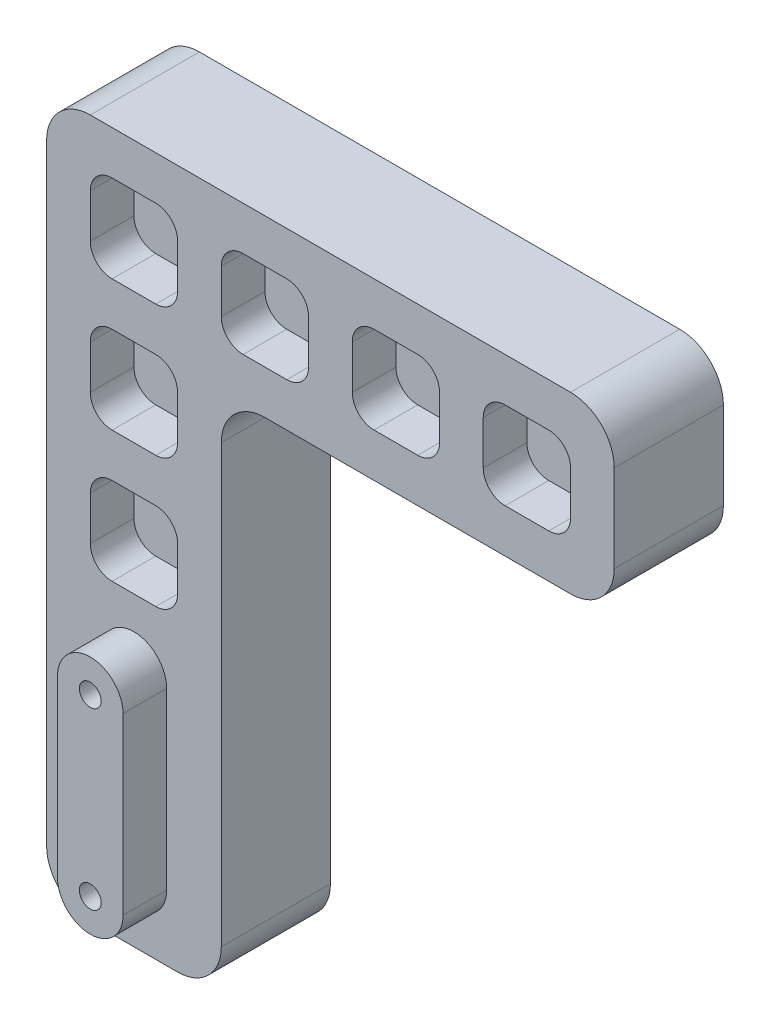
SolidWorks part; units mm, degrees
material "ABS"
ref_plane "Front Plane" through (0, 0, 0) normal (0, 0, 1) x (1, 0, 0)
ref_plane "Top Plane" through (0, 0, 0) normal (0, 1, 0) x (1, 0, 0)
ref_plane "Right Plane" through (0, 0, 0) normal (1, 0, 0) x (0, 0, -1)
sketch "Base Sketch" plane through (0, 0, 0) normal (0, 0, 1) x (1, 0, 0)
  line L0 (0, 0) -> (0, 160)
  line L1 (0, 160) -> (130, 160)
  line L2 (130, 160) -> (130, 120)
  line L3 (130, 120) -> (40, 120)
  line L4 (40, 120) -> (40, 0)
  line L5 (40, 0) -> (0, 0)
  dimension "D1" = 130
  dimension "D2" = 160
  dimension "D3" = 120
  dimension "D4" = 40
extrude "Base Extrude" add sketch "Base Sketch" along normal blind 25
sketch "Square Sketch" plane through (0, 0, 25) normal (0, 0, 1) x (1, 0, 0)
  line L0 (0, 160) -> (0, 0) construction
  line L1 (15, 150) -> (25, 150)
  line L2 (10, 145) -> (10, 135)
  line L3 (15, 130) -> (25, 130)
  line L4 (30, 145) -> (30, 135)
  line L5 (130, 160) -> (0, 160) construction
  arc A0 (25, 130) -> (30, 135) centre (25, 135) ccw
  arc A1 (15, 150) -> (10, 145) centre (15, 145) ccw
  arc A2 (15, 130) -> (10, 135) centre (15, 135) cw
  arc A3 (30, 145) -> (25, 150) centre (25, 145) ccw
  point P10 (30, 130)
  point P15 (10, 130)
  point P18 (30, 150)
  dimension "D5" = 5
  dimension "D1" = 10
  dimension "D2" = 10
  dimension "D3" = 20
  dimension "D4" = 20
extrude "Square Cut" cut sketch "Square Sketch" against normal blind 10
pattern_linear "Horizontal Pattern" count 4 spacing 30 along (1, 0, 0) of "Square Cut"
pattern_linear "Vertical Pattern" count 3 spacing 30 along (0, -1, 0) of "Square Cut"
sketch "Slot Sketch" plane through (0, 0, 25) normal (0, 0, 1) x (1, 0, 0)
  line L0 (20, 15) -> (20, 55) construction
  line L1 (12.5, 15) -> (12.5, 55)
  line L2 (27.5, 15) -> (27.5, 55)
  line L4 (0, 0) -> (40, 0) construction
  line L5 (40, 0) -> (40, 120) construction
  arc A0 (12.5, 15) -> (27.5, 15) centre (20, 15) ccw
  arc A1 (27.5, 55) -> (12.5, 55) centre (20, 55) ccw
  point P2 (20, 35)
  dimension "D1" = 40
  dimension "D2" = 15
  dimension "D3" = 15
  dimension "D4" = 12.5
extrude "Slot Extrude" add sketch "Slot Sketch" along normal blind 10
hole_wizard "M6x1.0 Slot Holes" positions "Hole Sketch" profile "Vertical Sketch" tap size "M6x1.0" standard "ANSI Metric" end condition through all
sketch "Hole Sketch" plane through (0, 0, 35) normal (0, 0, 1) x (1, 0, 0)
  point P0 (20, 55)
  point P3 (20, 15)
sketch "Vertical Sketch" plane through (20, 55, 35) normal (1, 0, 0) x (0, -1, 0)
  line L0 (0, 0) -> (0, 35)
  line L1 (0, 35) -> (2.5, 35)
  line L2 (2.5, 35) -> (2.5, 0)
  line L5 (2.5, 0) -> (0, 0)
  line L11 (0, -6.35) -> (0, 107.95) construction
  dimension "Thru Tap Drill Dia." = 5
  dimension "Thru Tap Drill Depth" = 35
cosmetic thread "Hole Thread 1" parameters "D2"=6
cosmetic thread "Hole Thread 2" parameters "D2"=6
fillet "Edge Fillets" radius 10 6 edges at (0, 160, 12.5) (130, 160, 12.5) (130, 120, 12.5) (40, 120, 12.5) (0, 0, 12.5) (40, 0, 12.5)
